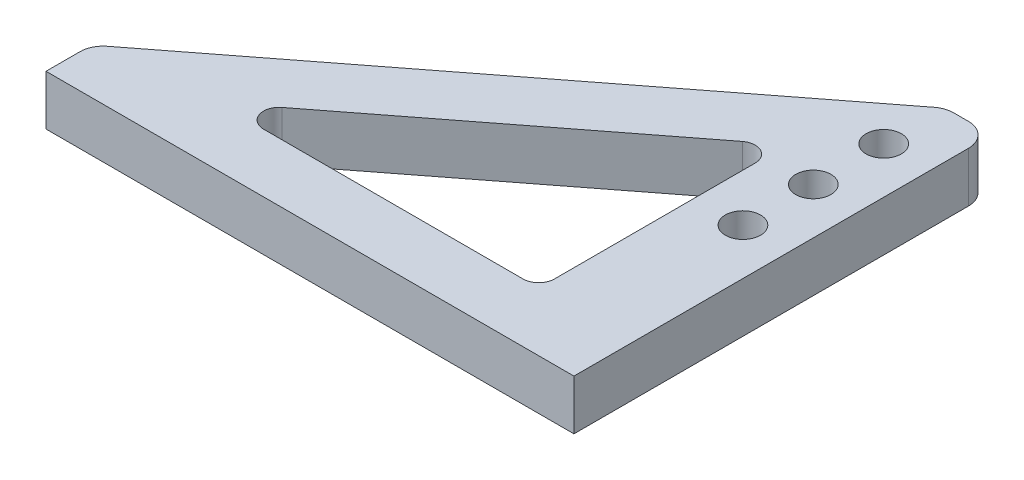
SolidWorks part; units mm, degrees
material "Delrin 2700 NC010, Low Viscosity Acetal Copolymer (SS)"
ref_plane "Front Plane" through (0, 0, 0) normal (0, 0, 1) x (1, 0, 0)
ref_plane "Top Plane" through (0, 0, 0) normal (0, 1, 0) x (1, 0, 0)
ref_plane "Right Plane" through (0, 0, 0) normal (1, 0, 0) x (0, 0, -1)
sketch "Sketch1" plane through (0, 0, 0) normal (0, 1, 0) x (1, 0, 0)
  line L0 (1.905, 1.4732) -> (17.5479, 13.5703)
  line L1 (1.905, 0) -> (19.05, 0)
  line L2 (5.5774, 1.905) -> (16.002, 1.905)
  line L3 (16.002, 1.905) -> (16.002, 9.9667)
  line L4 (19.05, 0) -> (19.05, 13.5703)
  line L5 (5.5774, 1.905) -> (16.002, 9.9667)
  line L6 (17.145, 1.905) -> (17.145, 10.8506) construction
  line L7 (5.5774, 1.905) -> (17.145, 10.8506) construction
  line L8 (5.5774, 1.905) -> (17.145, 1.905) construction
  line L9 (17.5479, 13.5703) -> (19.05, 13.5703)
  line L10 (19.05, 0) -> (19.05, 14.732) construction
  line L11 (0, 0) -> (19.05, 14.732) construction
  line L12 (1.905, 0) -> (1.905, 1.4732)
  line L13 (0, 0) -> (19.05, 0) construction
  circle A0 centre (17.5479, 11.5622) radius 0.5715
  circle A3 centre (17.5479, 9.2762) radius 0.5715
  circle A4 centre (17.5479, 6.9902) radius 0.5715
  dimension "D5" = 1.143
  dimension "D6" = 3
  dimension "D1" = 17.145
  dimension "D2" = 13.5703
  dimension "D4" = 3.048
  dimension "D3" = 1.905
extrude "Boss-Extrude1" add sketch "Sketch1" along normal blind 1.6256
fillet "Fillet1" radius 0.508 3 edges at (5.5774, 0.8128, -1.905) (16.002, 0.8128, -1.905) (16.002, 0.8128, -9.9667)
fillet "Fillet2" radius 0.762 3 edges at (1.905, 0.8128, -1.4732) (17.5479, 0.8128, -13.5703) (19.05, 0.8128, -13.5703)
